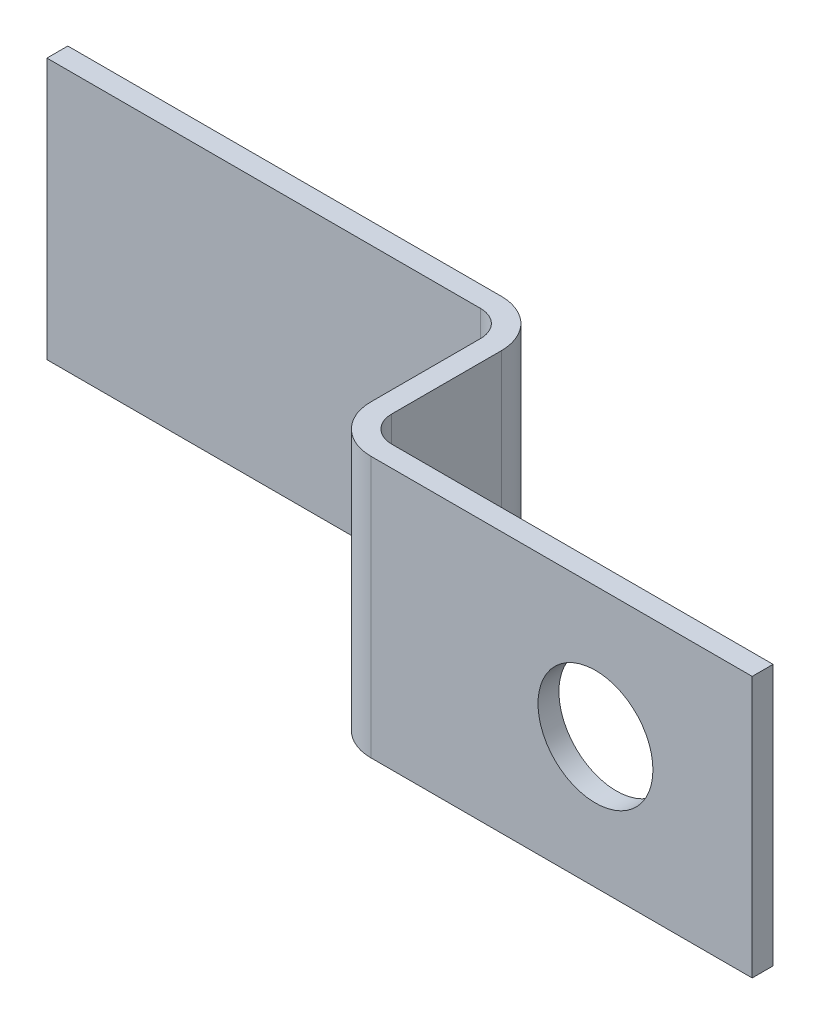
SolidWorks part; units mm, degrees
ref_plane "Front Plane" through (0, 0, 0) normal (0, 0, 1) x (1, 0, 0)
ref_plane "Top Plane" through (0, 0, 0) normal (0, 1, 0) x (1, 0, 0)
ref_plane "Right Plane" through (0, 0, 0) normal (1, 0, 0) x (0, 0, -1)
ref_plane "Plane1" through (0, 0, 4.4848) normal (0, 0, 1) x (1, 0, 0)
sketch "Sketch1" plane through (0, 0, 4.4848) normal (0, 0, 1) x (1, 0, 0)
  line L0 (-27.4626, 5) -> (-61.4626, 5)
  line L1 (-61.4626, 5) -> (-61.4626, -5)
  line L2 (-61.4626, -5) -> (-27.4626, -5)
  line L3 (-27.4626, -5) -> (-27.4626, 5)
extrude "Boss-Extrude1" add sketch "Sketch1" against normal blind 7.8
sketch "Sketch2" plane through (0, 5, 0) normal (0, 1, 0) x (-1, 0, 0)
  line L0 (43.0626, -3.3152) -> (43.0626, 3.6848)
  line L1 (43.0626, 3.6848) -> (27.4626, 3.6848)
  line L2 (27.4626, 3.6848) -> (27.4626, -3.3152)
  line L3 (27.4626, -3.3152) -> (43.0626, -3.3152)
extrude "Cut-Extrude1" cut sketch "Sketch2" against normal through all
sketch "Sketch3" plane through (0, 5, 0) normal (0, 1, 0) x (-1, 0, 0)
  line L0 (43.8626, 4.4848) -> (43.8626, -2.5152)
  line L1 (43.8626, -2.5152) -> (61.4626, -2.5152)
  line L2 (61.4626, -2.5152) -> (61.4626, 4.4848)
  line L3 (61.4626, 4.4848) -> (43.8626, 4.4848)
extrude "Cut-Extrude2" cut sketch "Sketch3" against normal through all
hole_wizard "Hole1" positions "Sketch5" profile "Sketch4" legacy
sketch "Sketch5" plane through (0, 0, 4.4848) normal (0, 0, 1) x (1, 0, 0)
  point P0 (-33.4626, 0)
sketch "Sketch4" plane through (-33.4626, 0, 4.4848) normal (1, 0, 0) x (0, -1, 0)
  line L0 (0, 0) -> (0, 7.8)
  line L1 (0, 7.8) -> (2.2, 7.8)
  line L2 (2.2, 7.8) -> (2.2, 0)
  line L3 (2.2, 0) -> (0, 0)
  line L4 (0, 110) -> (0, -10) construction
  dimension "Diameter" = 4.4
  dimension "Depth" = 7.8
fillet "Fillet1" radius 1 1 edges at (-43.0626, 0, 3.6848)
fillet "Fillet2" radius 1 1 edges at (-43.8626, 0, -2.5152)
fillet "Fillet3" radius 1.8 1 edges at (-43.0626, 0, -3.3152)
fillet "Fillet4" radius 1.8 1 edges at (-43.8626, 0, 4.4848)
